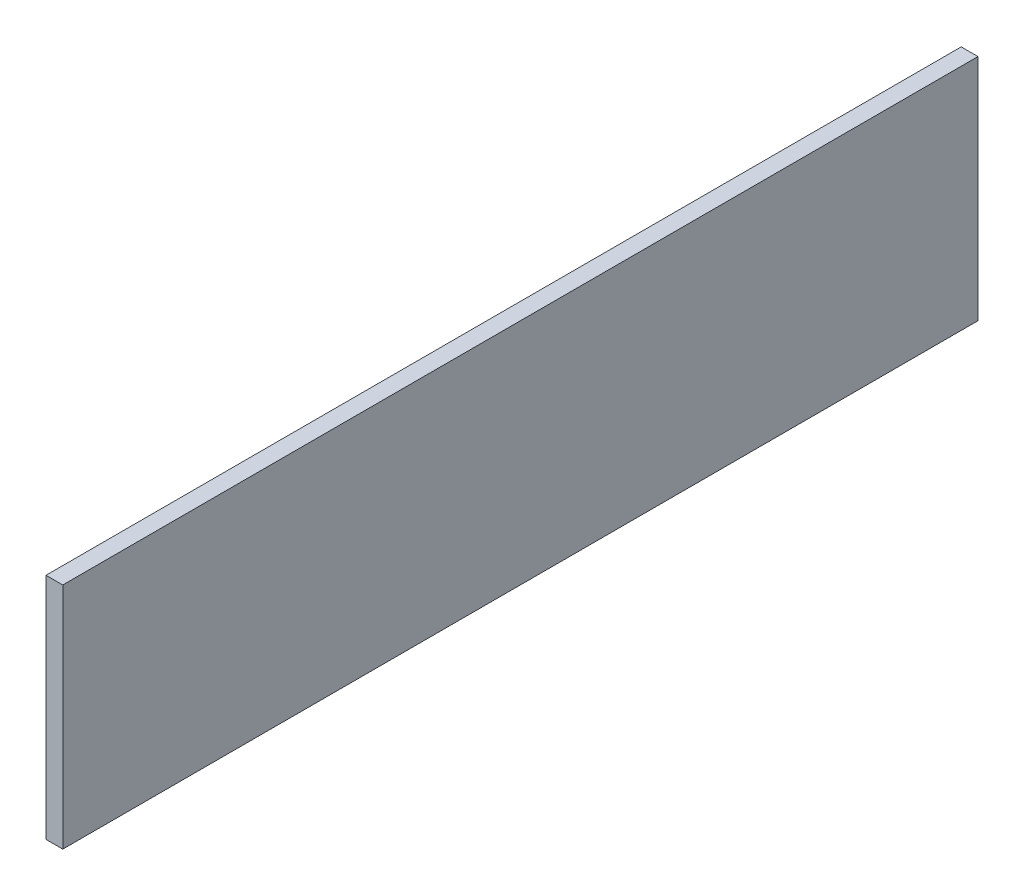
SolidWorks part; units mm, degrees
ref_plane "Front Plane" through (0, 0, 0) normal (0, 0, 1) x (1, 0, 0)
ref_plane "Top Plane" through (0, 0, 0) normal (0, 1, 0) x (1, 0, 0)
ref_plane "Right Plane" through (0, 0, 0) normal (1, 0, 0) x (0, 0, -1)
sketch "Sketch1" plane through (0, 0, 0) normal (1, 0, 0) x (0, 0, -1)
  line L1 (-152.4, -38.1) -> (152.4, -38.1)
  line L2 (-152.4, -38.1) -> (-152.4, 38.1)
  line L3 (-152.4, 38.1) -> (152.4, 38.1)
  line L4 (152.4, -38.1) -> (152.4, 38.1)
  line L5 (-152.4, -38.1) -> (152.4, 38.1) construction
  line L6 (-152.4, 38.1) -> (152.4, -38.1) construction
  point P0 (0, 0)
  dimension "D1" = 304.8
  dimension "D2" = 76.2
extrude "Boss-Extrude1" add sketch "Sketch1" along normal blind 5.588
